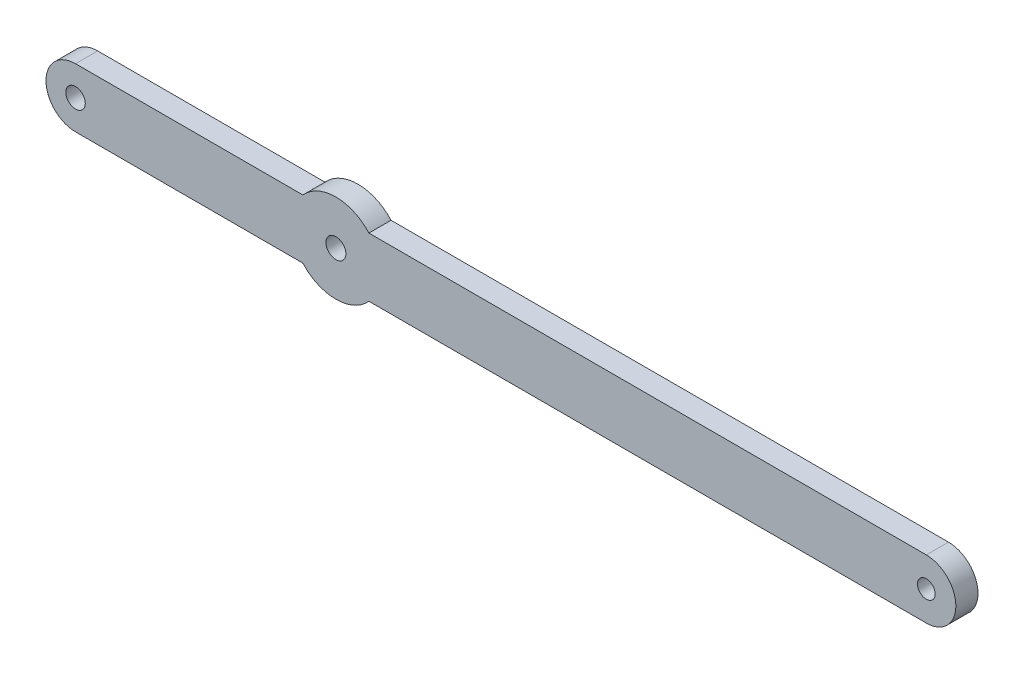
SolidWorks part; units mm, degrees
ref_plane "前视基准面" through (0, 0, 0) normal (0, 0, 1) x (1, 0, 0)
ref_plane "上视基准面" through (0, 0, 0) normal (0, 1, 0) x (1, 0, 0)
ref_plane "右视基准面" through (0, 0, 0) normal (1, 0, 0) x (0, 0, -1)
ref_plane "基准面1" through (0, 0, 0) normal (0, 0, -1) x (-1, 0, 0)
sketch "草图1" plane through (0, 0, 0) normal (0, 0, -1) x (-1, 0, 0)
  line L0 (91.2187, 7.5141) -> (60.4264, 7.5141)
  line L1 (51.4821, 7.5141) -> (-24.0198, 7.5141)
  line L2 (-24.0198, -0.4859) -> (51.4821, -0.4859)
  line L3 (60.4264, -0.4859) -> (91.2187, -0.4859)
  circle A0 centre (-24.0204, 3.5141) radius 1.2
  circle A1 centre (55.9543, 3.5141) radius 1.35
  circle A2 centre (91.2187, 3.5141) radius 1.32
  arc A3 (91.2187, -0.4859) -> (91.2187, 7.5141) centre (91.2187, 3.5141) ccw
  arc A4 (60.4264, 7.5141) -> (51.4821, 7.5141) centre (55.9543, 3.5141) ccw
  arc A5 (-24.0198, 7.5141) -> (-24.0198, -0.4859) centre (-24.0198, 3.5141) ccw
  arc A6 (51.4821, -0.4859) -> (60.4264, -0.4859) centre (55.9543, 3.5141) ccw
extrude "凸台-拉伸1" add sketch "草图1" against normal blind 3
